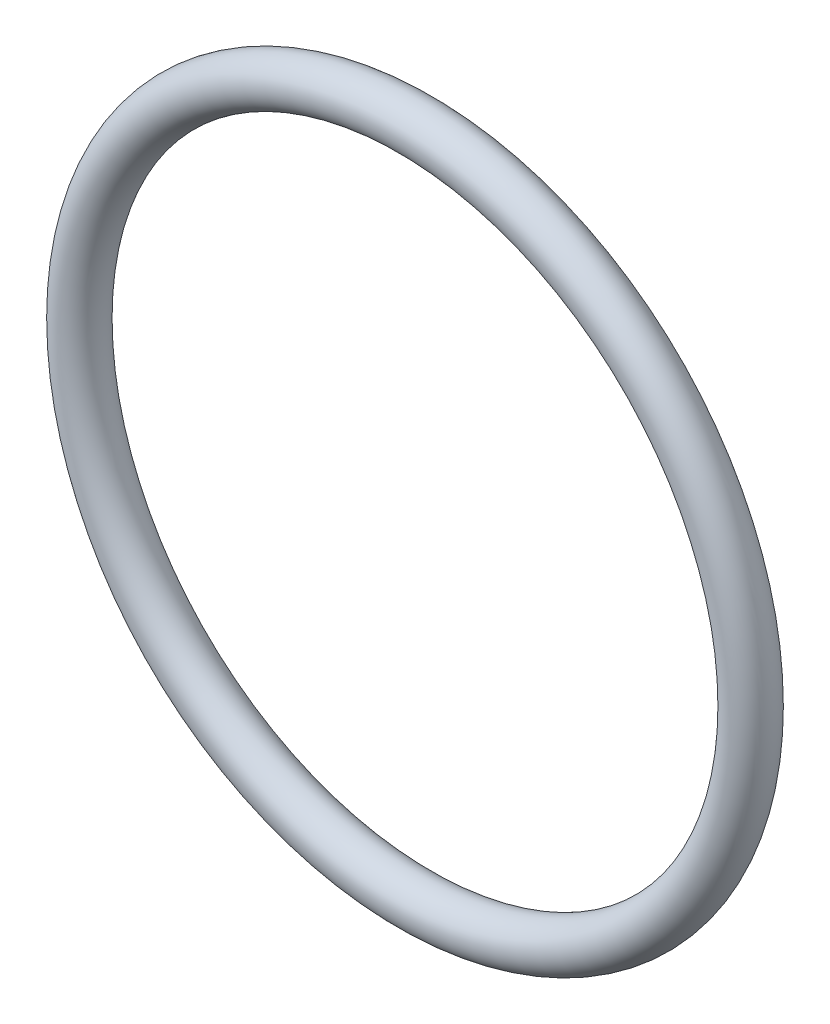
SolidWorks part; units mm, degrees
ref_plane "Front Plane" through (0, 0, 0) normal (0, 0, 1) x (1, 0, 0)
ref_plane "Top Plane" through (0, 0, 0) normal (0, 1, 0) x (1, 0, 0)
ref_plane "Right Plane" through (0, 0, 0) normal (1, 0, 0) x (0, 0, -1)
sketch "Sketch3" plane through (0, 0, 0) normal (0, 0, 1) x (1, 0, 0)
  circle A0 centre (0, 0) radius 29
  dimension "D1" = 58
sketch "Sketch4" plane through (0, 0, 0) normal (0, 1, 0) x (1, 0, 0)
  line L0 (-29, 0) -> (29, 0) construction
  circle A0 centre (-29, 0) radius 2
  point P4 (0, 0)
  dimension "D1" = 4
sweep "Sweep1" add profiles "Sketch4" path "Sketch3"
